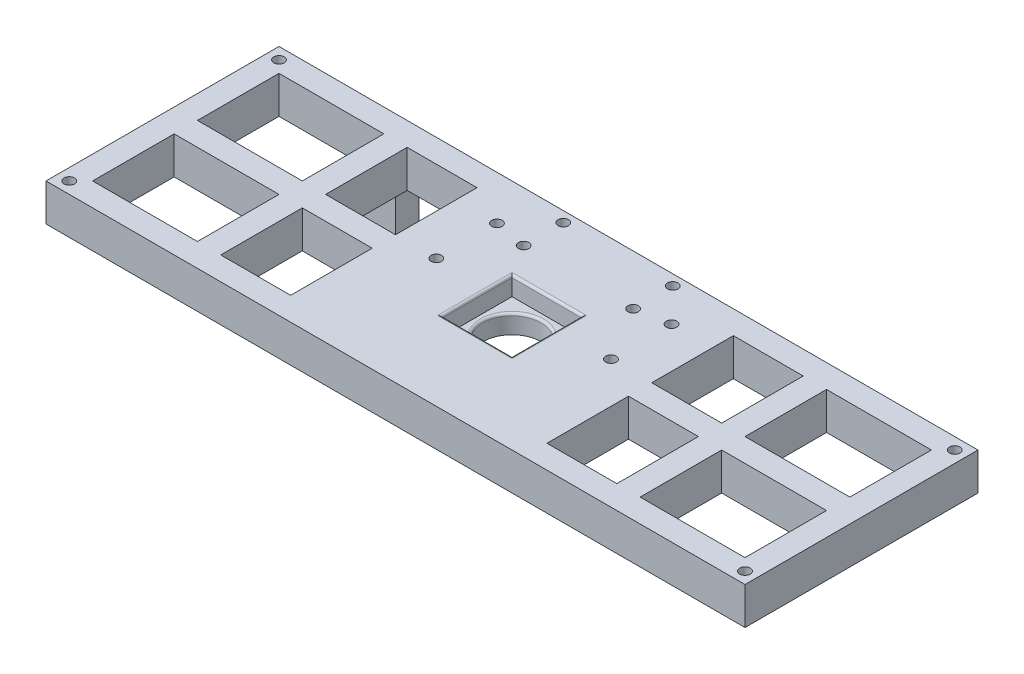
SolidWorks part; units mm, degrees
ref_plane "前视基准面" through (0, 0, 0) normal (0, 0, 1) x (1, 0, 0)
ref_plane "上视基准面" through (0, 0, 0) normal (0, 1, 0) x (1, 0, 0)
ref_plane "右视基准面" through (0, 0, 0) normal (1, 0, 0) x (0, 0, -1)
sketch "草图1" plane through (0, 0, 0) normal (0, 1, 0) x (1, 0, 0)
  line L1 (0, 0) -> (-300, 0)
  line L2 (0, 0) -> (0, 100)
  line L3 (0, 100) -> (-300, 100)
  line L4 (-300, 0) -> (-300, 100)
  dimension "D1" = 300
  dimension "D2" = 100
extrude "凸台-拉伸1" add sketch "草图1" along normal blind 16
sketch "草图2" plane through (0, 16, 0) normal (0, 1, 0) x (1, 0, 0)
  line L0 (-150, 100) -> (-150, 50) construction
  line L1 (0, 100) -> (-300, 100) construction
  line L2 (-300, 50) -> (-150, 50) construction
  line L3 (-300, 100) -> (-300, 0) construction
  line L5 (-165, 65) -> (-135, 65)
  line L6 (-165, 65) -> (-165, 35)
  line L7 (-165, 35) -> (-135, 35)
  line L8 (-135, 65) -> (-135, 35)
  line L9 (-165, 65) -> (-135, 35) construction
  line L10 (-165, 35) -> (-135, 65) construction
  dimension "D1" = 50
  dimension "D2" = 30
  dimension "D3" = 30
extrude "切除-拉伸1" cut sketch "草图2" against normal blind 8
sketch "草图3" plane through (0, 8, 0) normal (0, 1, 0) x (1, 0, 0)
  line L0 (-135, 65) -> (-165, 65) construction
  line L1 (-135, 35) -> (-135, 65) construction
  circle A0 centre (-150, 50) radius 12.5
  dimension "D3" = 25
  dimension "D1" = 15
  dimension "D2" = 15
extrude "切除-拉伸2" cut sketch "草图3" against normal blind 14
sketch "草图4" plane through (0, 16, 0) normal (0, 1, 0) x (1, 0, 0)
  line L0 (-165, 65) -> (-165, 35) construction
  line L1 (-295, 90) -> (-245, 90)
  line L2 (-295, 90) -> (-295, 55)
  line L3 (-295, 55) -> (-245, 55)
  line L4 (-245, 90) -> (-245, 55)
  line L5 (-295, 45) -> (-245, 45)
  line L6 (-295, 45) -> (-295, 10)
  line L7 (-295, 10) -> (-245, 10)
  line L8 (-245, 45) -> (-245, 10)
  line L9 (-235, 90) -> (-185, 90)
  line L10 (-235, 90) -> (-235, 55)
  line L11 (-235, 55) -> (-185, 55)
  line L12 (-185, 90) -> (-185, 55)
  line L13 (-235, 45) -> (-185, 45)
  line L14 (-235, 45) -> (-235, 10)
  line L15 (-235, 10) -> (-185, 10)
  line L16 (-185, 45) -> (-185, 10)
  line L17 (0, 100) -> (-300, 100) construction
  line L18 (-300, 0) -> (0, 0) construction
  line L19 (-300, 100) -> (-300, 0) construction
  line L20 (-150, 100) -> (-150, 73.2626) construction
  line L21 (-5, 10) -> (-55, 10)
  line L22 (-55, 45) -> (-55, 10)
  line L23 (-5, 45) -> (-55, 45)
  line L24 (-5, 45) -> (-5, 10)
  line L25 (-65, 10) -> (-115, 10)
  line L26 (-115, 45) -> (-115, 10)
  line L27 (-65, 45) -> (-115, 45)
  line L28 (-65, 45) -> (-65, 10)
  line L29 (-65, 55) -> (-115, 55)
  line L30 (-115, 90) -> (-115, 55)
  line L31 (-65, 90) -> (-115, 90)
  line L32 (-65, 90) -> (-65, 55)
  line L33 (-5, 55) -> (-55, 55)
  line L34 (-55, 90) -> (-55, 55)
  line L35 (-5, 90) -> (-55, 90)
  line L36 (-5, 90) -> (-5, 55)
  dimension "D1" = 20
  dimension "D2" = 20
  dimension "D3" = 10
  dimension "D4" = 10
  dimension "D5" = 10
  dimension "D6" = 35
  dimension "D7" = 10
  dimension "D8" = 10
  dimension "D9" = 5
  dimension "D10" = 5
  dimension "D11" = 35
  dimension "D12" = 35
  dimension "D13" = 50
  dimension "D14" = 50
  dimension "D15" = 50
  dimension "D16" = 50
extrude "切除-拉伸3" cut sketch "草图4" against normal up to next
sketch "草图7" plane through (-185, 0, 0) normal (-1, 0, 0) x (0, 0, 1)
  line L0 (-45, 0) -> (-10, 0) construction
  line L1 (-10, 0) -> (-10, 16) construction
  line L2 (-10, 16) -> (-45, 16) construction
  line L3 (-45, 16) -> (-45, 0) construction
  line L4 (-90, 0) -> (-55, 0) construction
  line L5 (-55, 0) -> (-55, 16) construction
  line L6 (-55, 16) -> (-90, 16) construction
  line L7 (-90, 16) -> (-90, 0) construction
  line L8 (-45, 0) -> (-10, 0)
  line L9 (-10, 0) -> (-10, 16)
  line L10 (-10, 16) -> (-45, 16)
  line L11 (-45, 16) -> (-45, 0)
  line L12 (-90, 0) -> (-55, 0)
  line L13 (-55, 0) -> (-55, 16)
  line L14 (-55, 16) -> (-90, 16)
  line L15 (-90, 16) -> (-90, 0)
extrude "凸台-拉伸2" add sketch "草图7" along normal blind 20
sketch "草图8" plane through (-115, 0, 0) normal (1, 0, 0) x (0, 0, -1)
  line L0 (10, 0) -> (45, 0) construction
  line L1 (45, 0) -> (45, 16) construction
  line L2 (45, 16) -> (10, 16) construction
  line L3 (10, 16) -> (10, 0) construction
  line L4 (55, 0) -> (90, 0) construction
  line L5 (90, 0) -> (90, 16) construction
  line L6 (90, 16) -> (55, 16) construction
  line L7 (55, 16) -> (55, 0) construction
  line L8 (10, 0) -> (45, 0)
  line L9 (45, 0) -> (45, 16)
  line L10 (45, 16) -> (10, 16)
  line L11 (10, 16) -> (10, 0)
  line L12 (55, 0) -> (90, 0)
  line L13 (90, 0) -> (90, 16)
  line L14 (90, 16) -> (55, 16)
  line L15 (55, 16) -> (55, 0)
extrude "凸台-拉伸3" add sketch "草图8" along normal blind 20
sketch "草图9" plane through (0, 0, 0) normal (0, -1, 0) x (1, 0, 0)
  line L5 (-295, -90) -> (-245, -90) construction
  line L10 (-260, -90) -> (-240, -90)
  line L20 (-260, -90) -> (-260, -100)
  line L21 (-260, -100) -> (-240, -100)
  line L22 (-240, -90) -> (-240, -100)
  line L23 (0, -100) -> (-300, -100) construction
  line L24 (-300, -100) -> (-300, 0) construction
  dimension "D3" = 20
  dimension "D4" = 40
extrude "凸台-拉伸4" add sketch "草图9" along normal blind 25
fillet "圆角1" radius 1 1 edges at (-150, 8, -37.5)
fillet "圆角2" radius 1 4 edges at (-135, 16, -50) (-150, 16, -65) (-150, 16, -35) (-165, 16, -50)
sketch "草图13" plane through (-5, 0, 0) normal (-1, 0, 0) x (0, 0, 1)
  line L0 (-90, 0) -> (-55, 0) construction
  line L1 (-55, 0) -> (-55, 16) construction
  line L2 (-55, 16) -> (-90, 16) construction
  line L3 (-90, 16) -> (-90, 0) construction
  line L4 (-45, 0) -> (-10, 0) construction
  line L5 (-10, 0) -> (-10, 16) construction
  line L6 (-10, 16) -> (-45, 16) construction
  line L7 (-45, 16) -> (-45, 0) construction
  line L8 (-90, 0) -> (-55, 0)
  line L9 (-55, 0) -> (-55, 16)
  line L10 (-55, 16) -> (-90, 16)
  line L11 (-90, 16) -> (-90, 0)
  line L12 (-45, 0) -> (-10, 0)
  line L13 (-10, 0) -> (-10, 16)
  line L14 (-10, 16) -> (-45, 16)
  line L15 (-45, 16) -> (-45, 0)
extrude "凸台-拉伸6" add sketch "草图13" along normal blind 4
sketch "草图14" plane through (-295, 0, 0) normal (1, 0, 0) x (0, 0, -1)
  line L0 (55, 0) -> (90, 0) construction
  line L1 (90, 0) -> (90, 16) construction
  line L2 (90, 16) -> (55, 16) construction
  line L3 (55, 16) -> (55, 0) construction
  line L4 (10, 0) -> (45, 0) construction
  line L5 (45, 0) -> (45, 16) construction
  line L6 (45, 16) -> (10, 16) construction
  line L7 (10, 16) -> (10, 0) construction
  line L8 (55, 0) -> (90, 0)
  line L9 (90, 0) -> (90, 16)
  line L10 (90, 16) -> (55, 16)
  line L11 (55, 16) -> (55, 0)
  line L12 (10, 0) -> (45, 0)
  line L13 (45, 0) -> (45, 16)
  line L14 (45, 16) -> (10, 16)
  line L15 (10, 16) -> (10, 0)
extrude "凸台-拉伸7" add sketch "草图14" along normal blind 4
sketch "草图17" plane through (-291, 0, 0) normal (1, 0, 0) x (0, 0, -1)
  line L0 (10, 16) -> (10, 0) construction
  line L1 (10, 0) -> (45, 0) construction
  line L2 (45, 0) -> (45, 16) construction
  line L3 (45, 16) -> (10, 16) construction
  line L4 (55, 16) -> (55, 0) construction
  line L5 (55, 0) -> (90, 0) construction
  line L6 (90, 0) -> (90, 16) construction
  line L7 (90, 16) -> (55, 16) construction
  line L8 (10, 16) -> (10, 0)
  line L9 (10, 0) -> (45, 0)
  line L10 (45, 0) -> (45, 16)
  line L11 (45, 16) -> (10, 16)
  line L12 (55, 16) -> (55, 0)
  line L13 (55, 0) -> (90, 0)
  line L14 (90, 0) -> (90, 16)
  line L15 (90, 16) -> (55, 16)
extrude "凸台-拉伸8" add sketch "草图17" along normal blind 1
sketch "草图18" plane through (-9, 0, 0) normal (-1, 0, 0) x (0, 0, 1)
  line L0 (-45, 16) -> (-45, 0) construction
  line L1 (-45, 0) -> (-10, 0) construction
  line L2 (-10, 0) -> (-10, 16) construction
  line L3 (-10, 16) -> (-45, 16) construction
  line L4 (-90, 16) -> (-90, 0) construction
  line L5 (-90, 0) -> (-55, 0) construction
  line L6 (-55, 0) -> (-55, 16) construction
  line L7 (-55, 16) -> (-90, 16) construction
  line L8 (-45, 16) -> (-45, 0)
  line L9 (-45, 0) -> (-10, 0)
  line L10 (-10, 0) -> (-10, 16)
  line L11 (-10, 16) -> (-45, 16)
  line L12 (-90, 16) -> (-90, 0)
  line L13 (-90, 0) -> (-55, 0)
  line L14 (-55, 0) -> (-55, 16)
  line L15 (-55, 16) -> (-90, 16)
extrude "凸台-拉伸9" add sketch "草图18" along normal blind 1
sketch "草图19" plane through (0, 16, 0) normal (0, 1, 0) x (1, 0, 0)
  line L0 (-300, 100) -> (-295, 100) construction
  line L1 (0, 100) -> (-300, 100) construction
  line L2 (-295, 100) -> (-295, 95) construction
  line L3 (-150, 100) -> (-150, 83.4567) construction
  line L4 (-300, 50) -> (-202.8605, 50) construction
  line L5 (-300, 100) -> (-300, 0) construction
  line L6 (-150, 0) -> (-150, 22.48) construction
  line L7 (-300, 0) -> (0, 0) construction
  line L8 (-5, 100) -> (-5, 95) construction
  line L9 (0, 100) -> (-5, 100) construction
  circle A0 centre (-295, 95) radius 2.25
  circle A1 centre (-295, 5) radius 2.25
  circle A4 centre (-5, 5) radius 2.25
  circle A5 centre (-5, 95) radius 2.25
  dimension "D3" = 4.5
  dimension "D1" = 5
  dimension "D2" = 5
extrude "切除-拉伸8" cut sketch "草图19" against normal blind 5
sketch "草图20" plane through (0, 0, 0) normal (0, -1, 0) x (1, 0, 0)
  circle A2 centre (-295, -95) radius 2.25 construction
  circle A3 centre (-295, -5) radius 2.25 construction
  circle A6 centre (-295, -95) radius 2.25
  circle A7 centre (-295, -5) radius 2.25
  circle A8 centre (-5, -95) radius 2.25 construction
  circle A9 centre (-5, -5) radius 2.25 construction
  circle A10 centre (-5, -95) radius 2.25
  circle A11 centre (-5, -5) radius 2.25
extrude "切除-拉伸9" cut sketch "草图20" against normal blind 5
extrude "切除-拉伸10" cut sketch "草图21" against normal blind 5
sketch "草图21" plane through (-100.2762, 16, -200.0918) normal (0, 1, 0) x (-0.0018, 0, -1)
  circle A4 centre (-104.5433, 26.4163) radius 1.45
  circle A5 centre (-121.5433, 26.4476) radius 1.45
  circle A6 centre (-121.4568, 73.4475) radius 1.45
  circle A7 centre (-104.4568, 73.4162) radius 1.45
sketch "草图22" plane through (0, 16, 0) normal (0, 1, 0) x (1, 0, 0)
  circle A0 centre (-173.5, 95.5) radius 2.25
  circle A1 centre (-173.5, 78.5) radius 2.25
  circle A2 centre (-126.5, 95.5) radius 2.25
  circle A3 centre (-126.5, 78.5) radius 2.25
  dimension "D1" = 4.5
  dimension "D2" = 4.5
  dimension "D3" = 4.5
  dimension "D4" = 4.5
extrude "切除-拉伸11" cut sketch "草图22" against normal blind 5
extrude "切除-拉伸12" cut sketch "草图23" against normal blind 5
sketch "草图23" plane through (-100.2762, 16, -200.0918) normal (0, 1, 0) x (-0.0018, 0, -1)
  circle A4 centre (-119.0691, 12.4622) radius 1.45
  circle A5 centre (-145.069, 12.51) radius 1.45
  circle A6 centre (-144.931, 87.4716) radius 1.45
  circle A7 centre (-118.9311, 87.4237) radius 1.45
sketch "草图24" plane through (0, 16, 0) normal (0, 1, 0) x (1, 0, 0)
  circle A0 centre (-187.4808, 81) radius 2.25
  circle A1 centre (-187.4808, 55) radius 2.25
  circle A2 centre (-112.5192, 81) radius 2.25
  circle A3 centre (-112.5192, 55) radius 2.25
  dimension "D1" = 4.5
  dimension "D2" = 4.5
  dimension "D3" = 4.5
  dimension "D4" = 4.5
extrude "切除-拉伸13" cut sketch "草图24" against normal blind 5
